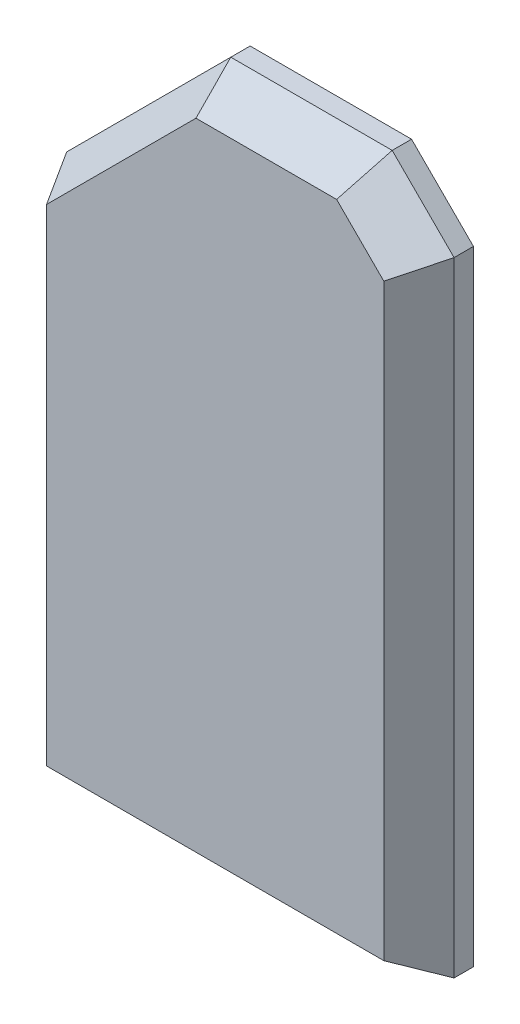
SolidWorks part; units mm, degrees
ref_plane "Front Plane" through (0, 0, 0) normal (0, 0, 1) x (1, 0, 0)
ref_plane "Top Plane" through (0, 0, 0) normal (0, 1, 0) x (1, 0, 0)
ref_plane "Right Plane" through (0, 0, 0) normal (1, 0, 0) x (0, 0, -1)
sketch "Sketch1" plane through (0, 0, 0) normal (0, 0, 1) x (1, 0, 0)
  line L0 (-57.8112, -26.0025) -> (-57.8112, 54.8034)
  line L1 (-57.8112, 54.8034) -> (-32.3981, 80.2165)
  line L2 (-32.3981, 80.2165) -> (-7.3981, 80.2165)
  line L3 (-7.3981, 80.2165) -> (2.1888, 70.6296)
  line L4 (2.1888, 70.6296) -> (2.1888, -26.0025)
  line L5 (2.1888, -26.0025) -> (-57.8112, -26.0025)
  dimension "D1" = 60
  dimension "D2" = 25
  dimension "D3" = 135
  dimension "D4" = 135
extrude "Boss-Extrude1" add sketch "Sketch1" along normal blind 7 draft 29 and the other way blind 3
sketch "Sketch2" plane through (0, 0, -3) normal (0, 0, -1) x (-1, 0, 0)
  line L0 (7.3981, 80.2165) -> (32.3981, 80.2165) construction
  circle A0 centre (19.8981, 56.2247) radius 1.5
  point P4 (19.8981, 80.2165)
  dimension "D1" = 3
extrude "Cut-Extrude1" cut sketch "Sketch2" against normal blind 3
